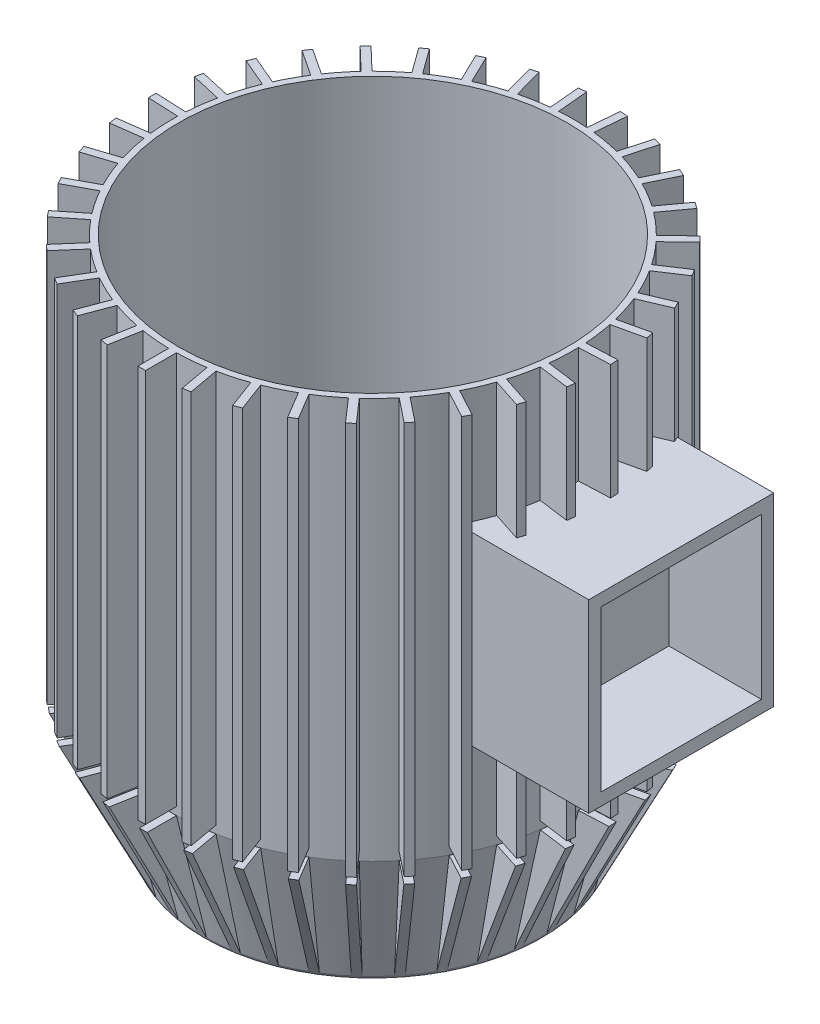
SolidWorks part; units mm, degrees
ref_plane "Front Plane" through (0, 0, 0) normal (0, 0, 1) x (1, 0, 0)
ref_plane "Top Plane" through (0, 0, 0) normal (0, 1, 0) x (1, 0, 0)
ref_plane "Right Plane" through (0, 0, 0) normal (1, 0, 0) x (0, 0, -1)
sketch "Sketch1" plane through (0, 0, 0) normal (0, 1, 0) x (1, 0, 0)
  circle A0 centre (0, 0) radius 65
  dimension "D1" = 130
extrude "Boss-Extrude1" add sketch "Sketch1" against normal blind 170
chamfer "Chamfer1" distance 10 distance2 40 1 edges at (0, -170, 65)
shell "Shell1" thickness 2
ref_plane "Plane1" through (0, 0, 75) normal (0, 0, 1) x (1, 0, 0)
sketch "Sketch2" plane through (0, 0, 75) normal (0, 0, 1) x (1, 0, 0)
  line L0 (63, 0) -> (-63, 0) construction
  line L1 (-1.25, 0) -> (1.25, 0)
  line L2 (-1.25, 0) -> (-1.25, -170)
  line L3 (-1.25, -170) -> (1.25, -170)
  line L4 (1.25, 0) -> (1.25, -170)
  line L5 (-55, -170) -> (55, -170) construction
  line L6 (0, 0) -> (0, -183.0943) construction
  dimension "D1" = 2.5
extrude "Boss-Extrude2" add sketch "Sketch2" against normal up to next
pattern_circular "CirPattern1" count 35 over 360 about axis through (0, 0, 0) along (0, 1, 0) of "Boss-Extrude2"
sketch "Sketch3" plane through (0, 0, 0) normal (0, 0, 1) x (1, 0, 0)
  line L0 (54.828, -170) -> (80.9365, -178.7485)
  line L1 (54.656, -170) -> (55, -170) construction
  line L2 (65, -127.5) -> (80.9365, -127.5)
  line L3 (54.828, -170) -> (74.489, -130)
  line L6 (65, -130) -> (74.489, -130)
  line L7 (64.5676, -130) -> (65, -130) construction
  line L8 (65, -130) -> (65, -127.5)
  line L9 (74.489, -170) -> (74.489, 0) construction
  line L11 (80.9365, -127.5) -> (80.9365, -178.7485)
  line L12 (0, 0) -> (0, -191.3981) construction
  dimension "D1" = 2.5
revolve "Cut-Revolve1" cut sketch "Sketch3" angle 360 about L12
sketch "Sketch4" plane through (0, -170, 0) normal (0, -1, 0) x (1, 0, 0)
  circle A0 centre (0, 0) radius 10
  dimension "D1" = 20
extrude "Cut-Extrude1" cut sketch "Sketch4" against normal through all
ref_plane "Plane2" through (100, 0, 0) normal (1, 0, 0) x (0, 0, -1)
sketch "Sketch5" plane through (100, 0, 0) normal (1, 0, 0) x (0, 0, -1)
  line L1 (-30, -37.5) -> (30, -37.5)
  line L2 (-30, -37.5) -> (-30, -97.5)
  line L3 (-30, -97.5) -> (30, -97.5)
  line L4 (30, -37.5) -> (30, -97.5)
  line L5 (0, 0) -> (0, -190.3217) construction
  dimension "D1" = 60
  dimension "D2" = 60
  dimension "D3" = 30
extrude "Boss-Extrude3" add sketch "Sketch5" against normal up to next
sketch "Sketch6" plane through (100, 0, 0) normal (1, 0, 0) x (0, 0, -1)
  line L0 (-26, -41.5) -> (-26, -93.5)
  line L1 (-26, -93.5) -> (26, -93.5)
  line L2 (26, -93.5) -> (26, -41.5)
  line L3 (26, -41.5) -> (-26, -41.5)
  line L4 (-30, -37.5) -> (-30, -97.5)
  line L5 (-30, -97.5) -> (30, -97.5)
  line L6 (30, -97.5) -> (30, -37.5)
  line L7 (30, -37.5) -> (-30, -37.5)
  line L8 (-30, -37.5) -> (-30, -97.5)
  line L9 (-30, -97.5) -> (30, -97.5)
  line L10 (30, -97.5) -> (30, -37.5)
  line L11 (30, -37.5) -> (-30, -37.5)
  dimension "D1" = 0
  dimension "D2" = 4
extrude "Cut-Extrude2" cut sketch "Sketch6" against normal blind 30 contours L0 L1 L2 L3
